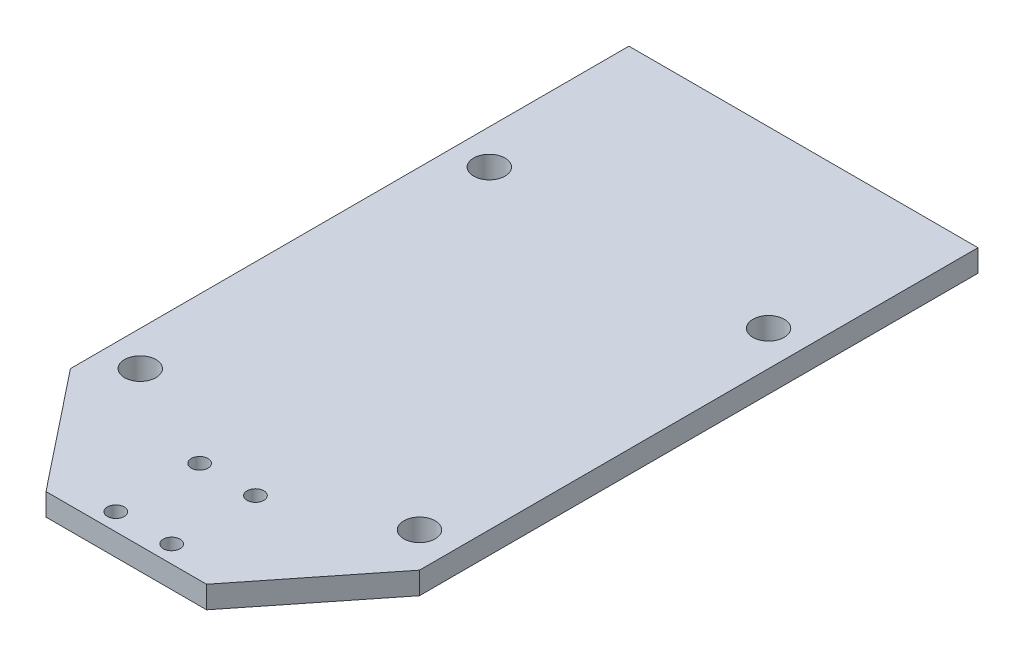
SolidWorks part; units mm, degrees
material "6061-T6 (SS)"
ref_plane "Front Plane" through (0, 0, 0) normal (0, 0, 1) x (1, 0, 0)
ref_plane "Top Plane" through (0, 0, 0) normal (0, 1, 0) x (1, 0, 0)
ref_plane "Right Plane" through (0, 0, 0) normal (1, 0, 0) x (0, 0, -1)
sketch "Sketch1" plane through (0, 0, 0) normal (0, 1, 0) x (1, 0, 0)
  line L0 (-11.5, -57) -> (-25, -40)
  line L1 (25, -40) -> (-25, -40)
  line L2 (25, -40) -> (25, 40)
  line L3 (25, 40) -> (-25, 40)
  line L4 (-25, -40) -> (-25, 40)
  line L5 (25, -40) -> (-25, 40) construction
  line L6 (25, 40) -> (-25, -40) construction
  line L7 (-11.5, -40) -> (11.5, -40)
  line L8 (-11.5, -40) -> (-11.5, -57)
  line L9 (-11.5, -57) -> (11.5, -57)
  line L10 (11.5, -40) -> (11.5, -57)
  line L11 (11.5, -57) -> (25, -40)
  line L12 (-25, -40) -> (25, -40)
  line L13 (11.5, -57) -> (-11.5, -57)
  point P0 (0, 0)
  dimension "D1" = 80
  dimension "D2" = 50
  dimension "D3" = 23
  dimension "D4" = 17
  dimension "D5" = 13.5
extrude "Boss-Extrude1" add sketch "Sketch1" along normal mid plane 3.175 contours L8 L1 L0 | L10 L11 L1 | L4 L1 L2 L3 | L10 L1 L8 L9
sketch "Sketch4" plane through (0, 1.5875, 0) normal (0, 1, 0) x (1, 0, 0)
  line L0 (-11.5, -57) -> (11.5, -57) construction
  point P0 (-4, -54.5)
  point P2 (4, -54.5)
  point P4 (4, -42.5)
  point P6 (-4, -42.5)
  point P16 (0, -57)
  dimension "D1" = 8
  dimension "D2" = 12
  dimension "D3" = 4
  dimension "D4" = 2.5
hole_wizard "M2 Clearance Hole1" positions "Sketch4" profile "Sketch3" hole size "M2" standard "ANSI Metric" end condition through all
sketch "Sketch3" plane through (-4, 1.5875, 54.5) normal (1, 0, 0) x (0, 0, 1)
  line L0 (0, 0) -> (0, 3.175)
  line L1 (0, 3.175) -> (1.2, 3.175)
  line L2 (1.2, 3.175) -> (1.2, 0)
  line L5 (1.2, 0) -> (0, 0)
  line L11 (0, -6.35) -> (0, 107.95) construction
  dimension "Thru Hole Dia." = 2.4
  dimension "Thru Hole Depth" = 3.175
sketch "Sketch7" plane through (0, 1.5875, 0) normal (0, 1, 0) x (1, 0, 0)
  line L0 (-25, -40) -> (-25, 40) construction
  line L1 (25, -40) -> (25, 40) construction
  line L2 (25, 40) -> (-25, 40) construction
  point P0 (-20, 15)
  point P2 (20, 15)
  point P4 (20, -35)
  point P6 (-20, -35)
  point P9 (0, 0)
  point P10 (0, 0)
  point P11 (0, 0)
  point P12 (0, 0)
  point P13 (0, 0)
  dimension "D1" = 5
  dimension "D2" = 5
  dimension "D3" = 25
  dimension "D4" = 50
hole_wizard "M4 Clearance Hole1" positions "Sketch7" profile "Sketch6" hole size "M4" standard "ANSI Metric" end condition through all
sketch "Sketch6" plane through (-20, 1.5875, -15) normal (1, 0, 0) x (0, 0, 1)
  line L0 (0, 0) -> (0, 3.175)
  line L1 (0, 3.175) -> (2.25, 3.175)
  line L2 (2.25, 3.175) -> (2.25, 0)
  line L5 (2.25, 0) -> (0, 0)
  line L11 (0, -6.35) -> (0, 107.95) construction
  dimension "Thru Hole Dia." = 4.5
  dimension "Thru Hole Depth" = 3.175
